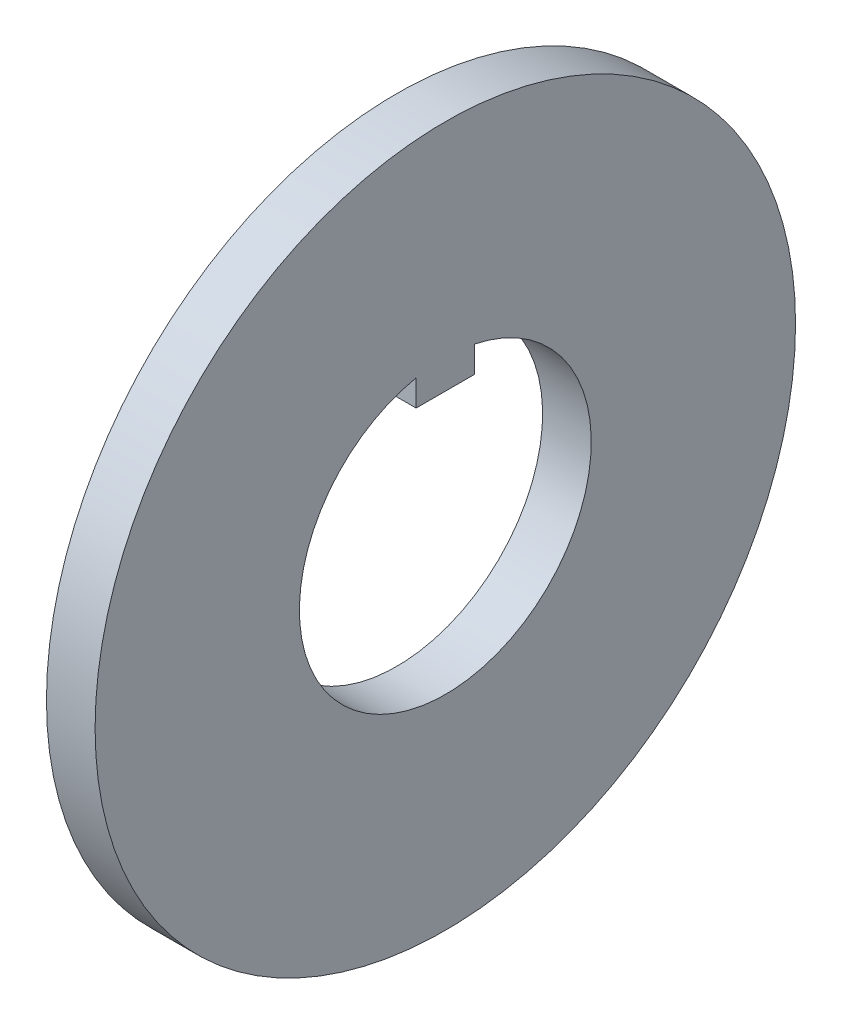
SolidWorks part; units mm, degrees
ref_plane "Front Plane" through (0, 0, 0) normal (0, 0, 1) x (1, 0, 0)
ref_plane "Top Plane" through (0, 0, 0) normal (0, 1, 0) x (1, 0, 0)
ref_plane "Right Plane" through (0, 0, 0) normal (1, 0, 0) x (0, 0, -1)
sketch "Sketch1" plane through (0, 0, 0) normal (1, 0, 0) x (0, 0, -1)
  circle A0 centre (0, 0) radius 91.44
  dimension "D1" = 182.88
extrude "Boss-Extrude1" add sketch "Sketch1" along normal blind 12.7
sketch "Sketch2" plane through (12.7, 0, 0) normal (1, 0, 0) x (0, 0, -1)
  line L0 (0, 0) -> (0, 91.44) construction
  line L6 (7.62, 30.48) -> (-7.62, 30.48)
  line L7 (7.62, 30.48) -> (7.62, 45.72)
  line L8 (7.62, 45.72) -> (-7.62, 45.72)
  line L9 (-7.62, 30.48) -> (-7.62, 45.72)
  line L10 (7.62, 30.48) -> (-7.62, 45.72) construction
  line L11 (7.62, 45.72) -> (-7.62, 30.48) construction
  circle A1 centre (0, 0) radius 91.44 construction
  arc A3 (7.62, 37.3302) -> (-7.62, 37.3302) centre (0, 0) cw
  point P8 (0, 38.1)
  point P13 (0, 0)
  point P14 (0, 0)
  point P15 (0, 0)
  point P18 (0, 0)
  dimension "D1" = 38.1
  dimension "D2" = 15.24
  dimension "D3" = 15.24
  dimension "D4" = 38.1
extrude "Cut-Extrude1" cut sketch "Sketch2" against normal blind 12.7 contours A3 L7 L6 L9
